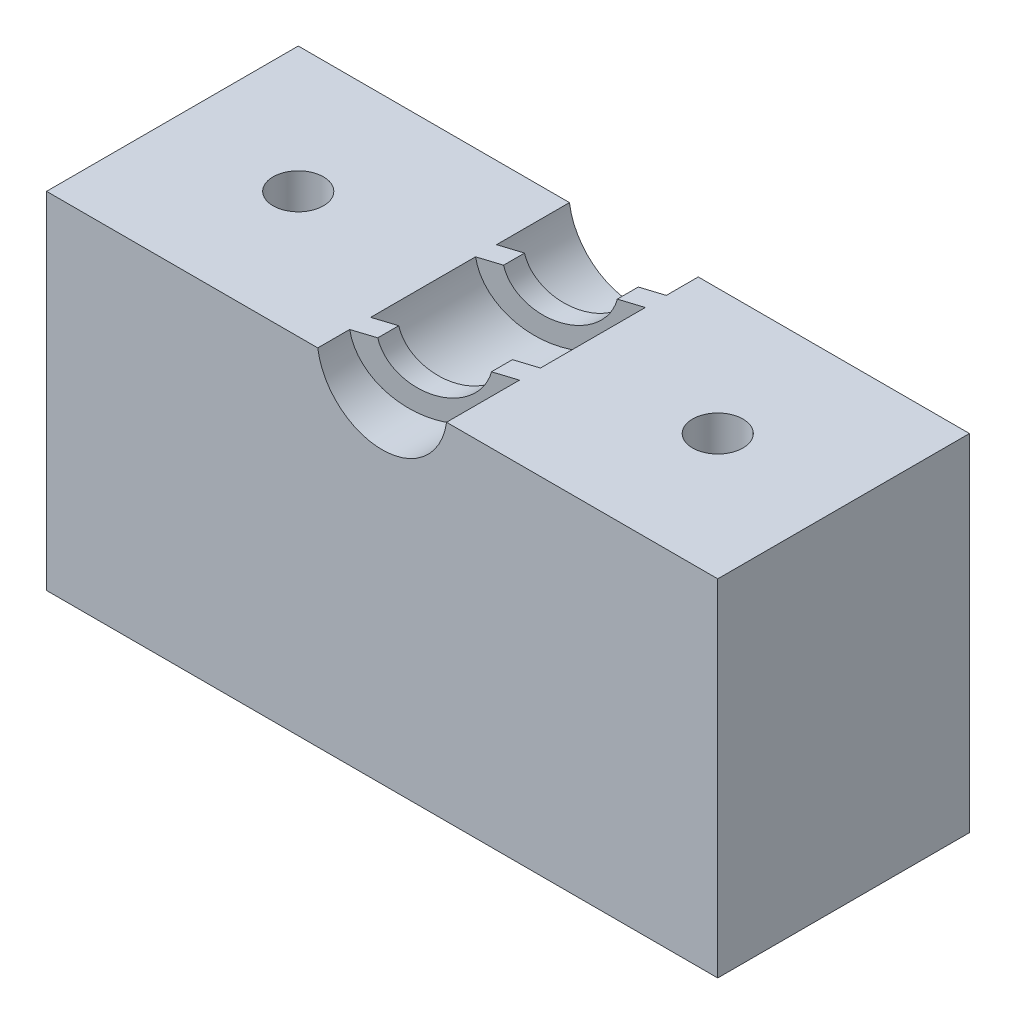
SolidWorks part; units mm, degrees
ref_plane "前视基准面" through (0, 0, 0) normal (0, 0, 1) x (1, 0, 0)
ref_plane "上视基准面" through (0, 0, 0) normal (0, 1, 0) x (1, 0, 0)
ref_plane "右视基准面" through (0, 0, 0) normal (1, 0, 0) x (0, 0, -1)
other "Configuration Table"
sketch "草图1" plane through (0, 0, 0) normal (0, 0, 1) x (1, 0, 0)
  line L1 (-8, -8) -> (8, -8)
  line L2 (-8, -8) -> (-8, 8)
  line L3 (-8, 8) -> (8, 8)
  line L4 (8, -8) -> (8, 8)
  line L5 (-8, -8) -> (8, 8) construction
  line L6 (-8, 8) -> (8, -8) construction
  circle A0 centre (0, 0) radius 1.55
  point P0 (0, 0)
  dimension "D3" = 3.1
  dimension "D1" = 16
  dimension "D2" = 16
extrude "凸台-拉伸1" add sketch "草图1" along normal mid plane 6
sketch "草图6" plane through (0, 0, 0) normal (0, 1, 0) x (1, 0, 0)
  line L0 (-1.55, -3) -> (1.55, -3) construction
  line L1 (1.55, 3) -> (-1.55, 3) construction
  line L2 (-1.55, -3) -> (1.55, -3)
  line L3 (1.55, 3) -> (-1.55, 3)
  line L4 (-1.55, 3) -> (-1.55, -3)
  line L5 (1.55, -3) -> (1.55, 3)
  line L6 (-1.55, 0.7565) -> (1.55, 1.7435)
  line L7 (1.55, 1.7435) -> (1.55, 2.2435)
  line L8 (1.55, 2.2435) -> (-1.55, 1.2565)
  line L9 (-1.55, -1.7435) -> (1.55, -0.7565)
  line L10 (-1.55, -2.2435) -> (1.55, -1.2565)
  line L11 (-2.0945, -0.6668) -> (3.135, 0.9981) construction
  line L12 (-3.1004, 0) -> (4.2723, 0) construction
  dimension "D1" = 2.5
  dimension "D2" = 0.5
  dimension "D3" = 0.5
  dimension "D4" = 17.66
extrude "凸台-拉伸2" add sketch "草图6" against normal up to surface (8 mm away) contours L4 L10 L5 L9 | L5 L8 L4 L6 up to face at (0, -8, 0)
sketch "草图7" plane through (0, 0, 0) normal (0, 0, 1) x (1, 0, 0)
  line L0 (0, 0) -> (-1.0279, -0.2141)
  line L1 (0, 0) -> (1.0279, -0.2141)
  line L2 (-1.0279, -0.2141) -> (-8, -0.2141)
  line L3 (1.0279, -0.2141) -> (8, -0.2141)
  line L6 (8, -8) -> (8, 8)
  line L7 (-8, -8) -> (8, -8)
  line L8 (-8, 8) -> (-8, -8)
  line L9 (8, 8) -> (-8, 8)
  line L10 (8, -8) -> (8, 8)
  line L11 (-8, -8) -> (8, -8)
  line L12 (-8, 8) -> (-8, -8)
  line L13 (8, 8) -> (-8, 8)
  circle A0 centre (0, 0) radius 1.05
  dimension "D1" = 2.1
  dimension "D2" = 0
  dimension "D3" = 156.47
extrude "切除-拉伸2" cut sketch "草图7" against normal through all both and the other way through all contours A0 L3 L10 L13 L12 L2 | L1 A0 L0 | L0 A0 L1
sketch "草图8" plane through (0, 0, 0) normal (0, 1, 0) x (1, 0, 0)
  line L0 (0, 5.5834) -> (0, -5.0797) construction
  circle A0 centre (-5, 0) radius 0.6
  circle A1 centre (5, 0) radius 0.6
  dimension "D2" = 1.2
  dimension "D3" = 10
extrude "切除-拉伸3" cut sketch "草图8" against normal through all
sketch "草图9" plane through (0, -8, 0) normal (0, -1, 0) x (1, 0, 0)
  line L4 (-8, -3) -> (8, -3)
  line L5 (8, -3) -> (8, 3)
  line L6 (8, 3) -> (-8, 3)
  line L7 (-8, 3) -> (-8, -3)
  line L8 (-8, -3) -> (8, -3)
  line L9 (8, -3) -> (8, 3)
  line L10 (8, 3) -> (-8, 3)
  line L11 (-8, 3) -> (-8, -3)
  circle A0 centre (-5, 0) radius 0.6 construction
  circle A1 centre (5, 0) radius 0.6 construction
  circle A2 centre (-5, 0) radius 0.6
  circle A3 centre (5, 0) radius 0.6
  dimension "D1" = 0
extrude "凸台-拉伸3" add sketch "草图9" along normal offset from surface (0.455 mm away) 0.5
equation "\"x\"=0.8094"
